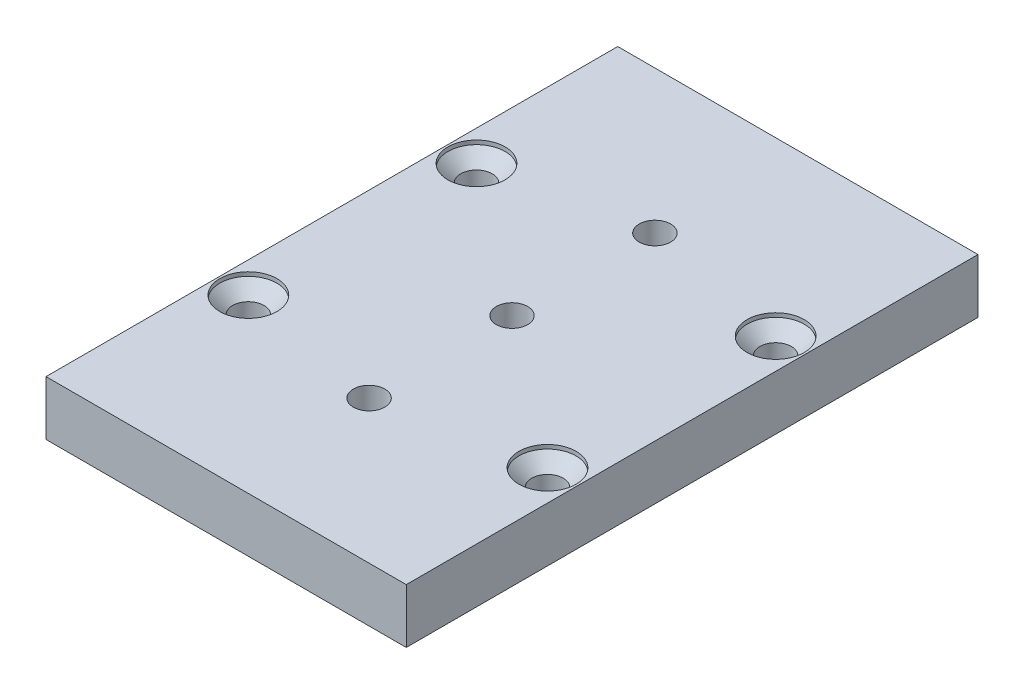
SolidWorks part; units mm, degrees
ref_plane "Plano frontal" through (0, 0, 0) normal (0, 0, 1) x (1, 0, 0)
ref_plane "Plano superior" through (0, 0, 0) normal (0, 1, 0) x (1, 0, 0)
ref_plane "Plano direito" through (0, 0, 0) normal (1, 0, 0) x (0, 0, -1)
sketch "Esboço1" plane through (0, 0, 0) normal (0, 1, 0) x (1, 0, 0)
  line L0 (31.505, 50) -> (-31.505, -50) construction
  line L1 (-31.505, 50) -> (31.505, 50)
  line L2 (-31.505, 50) -> (-31.505, -50)
  line L3 (-31.505, -50) -> (31.505, -50)
  line L4 (31.505, 50) -> (31.505, -50)
  dimension "D1" = 63.01
  dimension "D2" = 100
extrude "Ressalto-extrusão1" add sketch "Esboço1" along normal blind 9.525
sketch "Esboço2" plane through (0, 0, 0) normal (0, -1, 0) x (1, 0, 0)
  circle A0 centre (-26.16, 19.9509) radius 2.75
  circle A1 centre (0, 25) radius 2.75
  circle A2 centre (26.16, 19.9509) radius 2.75
  circle A3 centre (0, 0) radius 2.75
  circle A4 centre (-26.16, -19.95) radius 2.75
  circle A5 centre (0, -25) radius 2.75
  circle A6 centre (26.16, -19.95) radius 2.75
  dimension "D1" = 5.5
  dimension "D2" = 5.5
  dimension "D3" = 5.5
  dimension "D4" = 5.5
  dimension "D5" = 5.5
  dimension "D6" = 5.5
  dimension "D7" = 5.5
extrude "Corte-extrusão1" cut sketch "Esboço2" against normal blind 10
sketch "Esboço3" plane through (0, 9.525, 0) normal (0, 1, 0) x (1, 0, 0)
  circle A0 centre (26.16, 19.95) radius 5
  circle A1 centre (26.16, -19.9509) radius 5
  circle A2 centre (-26.16, -19.9509) radius 5
  circle A3 centre (-26.16, 19.95) radius 5
  dimension "D1" = 10
  dimension "D2" = 10
  dimension "D3" = 10
  dimension "D4" = 10
extrude "Corte-extrusão2" cut sketch "Esboço3" against normal blind 0.7
sketch "Esboço4" plane through (0, 8.825, 0) normal (0, 1, 0) x (1, 0, 0)
  circle A0 centre (26.16, 19.95) radius 5
  circle A1 centre (-26.16, 19.95) radius 5
  circle A2 centre (-26.16, -19.9509) radius 5
  circle A3 centre (26.16, -19.9509) radius 5
extrude "Corte-extrusão3" cut sketch "Esboço4" against normal blind 2.5 draft 45
